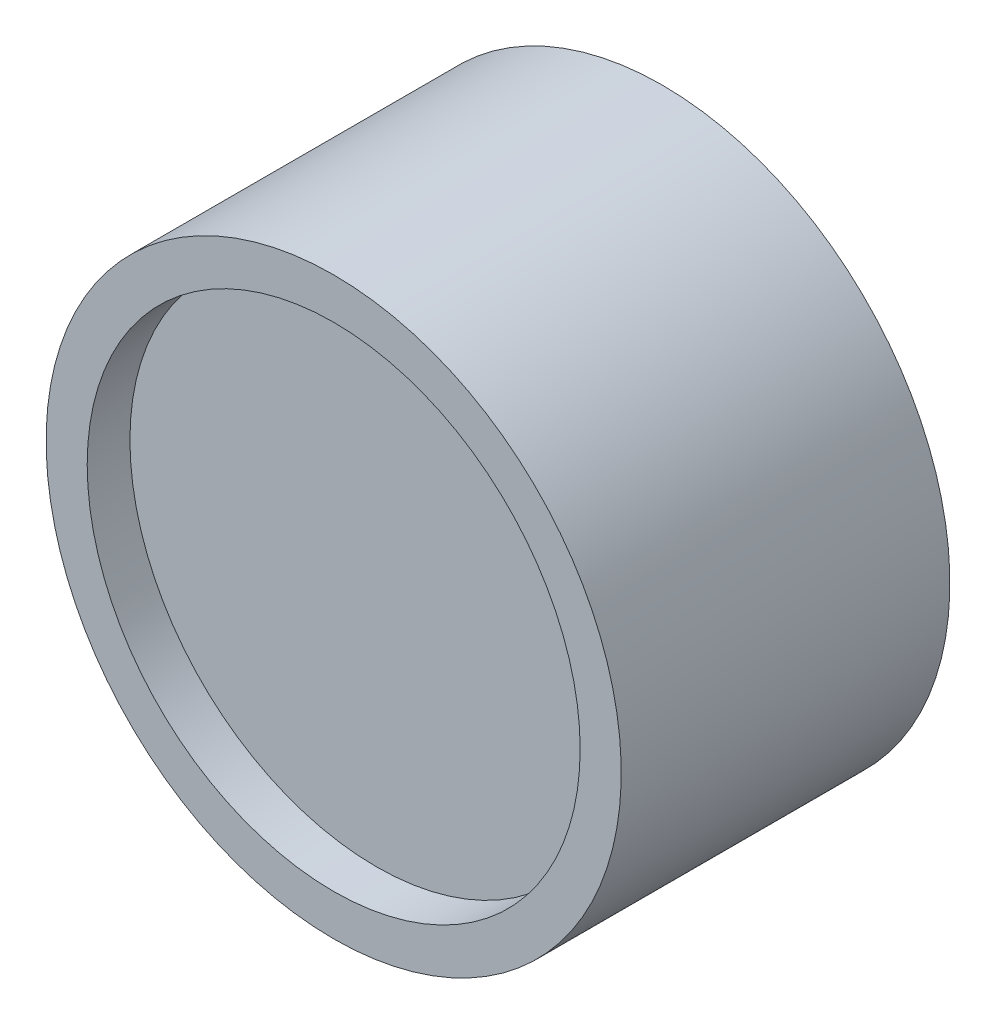
SolidWorks part; units mm, degrees
material "Cast Alloy Steel"
ref_plane "Front" through (0, 0, 0) normal (0, 0, 1) x (1, 0, 0)
ref_plane "Top" through (0, 0, 0) normal (0, 1, 0) x (1, 0, 0)
ref_plane "Right" through (0, 0, 0) normal (1, 0, 0) x (0, 0, -1)
sketch "Sketch1" plane through (0, 0, 0) normal (1, 0, 0) x (0, 0, -1)
  line L0 (-12.7, 19.05) -> (-9.398, 19.05)
  line L1 (-9.398, 19.05) -> (-9.398, 0)
  line L2 (-9.398, 0) -> (9.398, 0)
  line L3 (9.398, 0) -> (9.398, 19.05)
  line L4 (9.398, 19.05) -> (12.7, 19.05)
  line L5 (12.7, 19.05) -> (12.7, 22.225)
  line L6 (12.7, 22.225) -> (-12.7, 22.225)
  line L7 (-12.7, 22.225) -> (-12.7, 19.05)
  point P8 (0, 0)
  point P9 (5.5799, 0)
  point P11 (10.1195, 22.225)
  point P12 (5.4853, 13.8079)
  dimension "D1" = 22.225
  dimension "D2" = 19.05
  dimension "D3" = 25.4
  dimension "D4" = 3.302
revolve "Revolve1" add sketch "Sketch1" angle 360 about L2
ref_plane "Plane1" through (0, -22.225, 0) normal (0, -1, 0) x (-1, 0, 0)
hole_wizard "1/8 (0.125) Diameter Hole1" positions "Sketch3" profile "Sketch4" hole size "1/8" standard "ANSI Inch"
sketch "Sketch3" plane through (0, -22.225, 0) normal (0, -1, 0) x (-1, 0, 0)
  point P0 (0, 0)
sketch "Sketch4" plane through (0, -22.225, 0) normal (1, 0, 0) x (0, 0, -1)
  line L0 (0, 0) -> (0, 16.9559)
  line L1 (0, 16.9559) -> (1.5875, 16.002)
  line L2 (1.5875, 16.002) -> (1.5875, 0)
  line L5 (1.5875, 0) -> (0, 0)
  line L10 (0, 16.9559) -> (-1.5875, 16.002) construction
  line L11 (0, -6.35) -> (0, 107.95) construction
  dimension "Hole Dia." = 3.175
  dimension "Hole Depth" = 16.002
  dimension "Drill Angle" = 118
